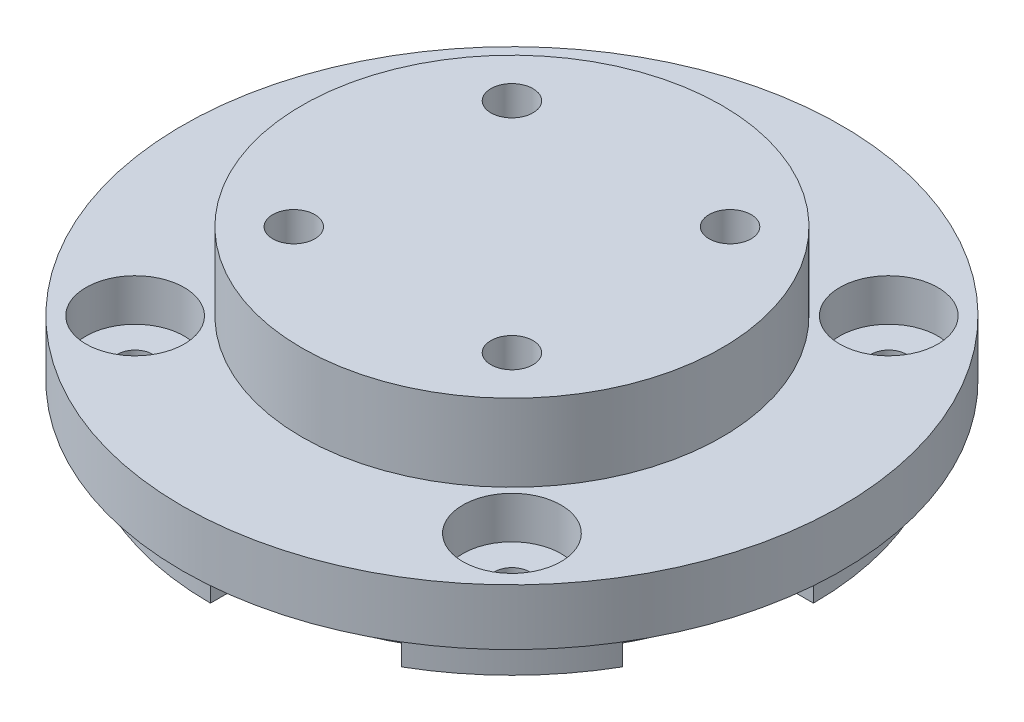
SolidWorks part; units mm, degrees
material "ABS"
ref_plane "前视基准面" through (0, 0, 0) normal (0, 0, 1) x (1, 0, 0)
ref_plane "上视基准面" through (0, 0, 0) normal (0, 1, 0) x (1, 0, 0)
ref_plane "右视基准面" through (0, 0, 0) normal (1, 0, 0) x (0, 0, -1)
other "Configuration Table"
sketch "草图2" plane through (0, 0, 0) normal (0, 1, 0) x (1, 0, 0)
  circle A0 centre (0, 0) radius 21.5
  dimension "D1" = 43
extrude "凸台-拉伸1" add sketch "草图2" along normal blind 7
sketch "草图3" plane through (0, 7, 0) normal (0, 1, 0) x (1, 0, 0)
  circle A0 centre (0, 0) radius 23.5
  circle A1 centre (0, 0) radius 21.5 construction
  dimension "D1" = 2
extrude "凸台-拉伸2" add sketch "草图3" against normal blind 4
sketch "草图6" plane through (0, 7, 0) normal (0, 1, 0) x (1, 0, 0)
  circle A0 centre (0, 0) radius 19 construction
  circle A1 centre (13.435, 13.435) radius 1.25
  circle A2 centre (13.435, -13.435) radius 1.25
  circle A3 centre (-13.435, -13.435) radius 1.25
  circle A4 centre (-13.435, 13.435) radius 1.25
  circle A5 centre (0, 0) radius 8
  dimension "D1" = 38
  dimension "D2" = 2.5
  dimension "D4" = 16
  dimension "D3" = 4
extrude "切除-拉伸1" cut sketch "草图6" against normal blind 15
sketch "草图7" plane through (0, 7, 0) normal (0, 1, 0) x (1, 0, 0)
  circle A0 centre (-13.435, 13.435) radius 3.5
  circle A1 centre (13.435, 13.435) radius 3.5
  circle A2 centre (13.435, -13.435) radius 3.5
  circle A3 centre (-13.435, -13.435) radius 3.5
  point P12 (0, 0)
  dimension "D1" = 7
  dimension "D2" = 4
sketch "草图9" plane through (0, 7, 0) normal (0, 1, 0) x (1, 0, 0)
  circle A0 centre (0, 0) radius 14.02
  circle A1 centre (0, 0) radius 14.98
  dimension "D1" = 28.04
  dimension "D2" = 29.96
extrude "凸台-拉伸3" add sketch "草图9" along normal blind 5.5
extrude "切除-拉伸3" cut sketch "草图7" against normal blind 3
sketch "草图10" plane through (0, 7, 0) normal (0, 1, 0) x (1, 0, 0)
  circle A0 centre (0, 0) radius 11 construction
  circle A3 centre (7.7782, 7.7782) radius 1.25
  circle A4 centre (7.7782, -7.7782) radius 1.25
  circle A5 centre (-7.7782, -7.7782) radius 1.25
  circle A6 centre (-7.7782, 7.7782) radius 1.25
  dimension "D1" = 22
  dimension "D2" = 2.5
  dimension "D3" = 4
extrude "切除-拉伸4" cut sketch "草图10" against normal blind 22
cosmetic thread "装饰螺纹线1" parameters "D2"=3
cosmetic thread "装饰螺纹线2" parameters "D2"=3
cosmetic thread "装饰螺纹线3" parameters "D2"=3
cosmetic thread "装饰螺纹线4" parameters "D2"=3
sketch "草图11" plane through (0, 0, 0) normal (0, -1, 0) x (1, 0, 0)
  line L0 (0, 0) -> (18.6195, 10.75)
  line L1 (0, 0) -> (21.5, 0)
  line L2 (0, 0) -> (0, 21.5)
  line L3 (10.75, 18.6195) -> (0, 0)
  circle A0 centre (0, 0) radius 19.5
  circle A1 centre (0, 0) radius 21.5 construction
  circle A2 centre (0, 0) radius 21.5
  circle M14 centre (0, 0) radius 21.5
  dimension "D1" = 39
  dimension "D2" = 30
  dimension "D3" = 30
extrude "切除-拉伸5" cut sketch "草图11" against normal up to surface (3 mm away) contours A0 L1 L0 M14 | A0 L3 L2 M14 up to face at (0, 3, 21.5)
sketch "草图12" plane through (0, 7, 0) normal (0, 1, 0) x (1, 0, 0)
  circle A0 centre (7.7782, 7.7782) radius 1.5
  circle A1 centre (7.7782, -7.7782) radius 1.5
  circle A2 centre (-7.7782, -7.7782) radius 1.5
  circle A3 centre (-7.7782, 7.7782) radius 1.5
  circle A4 centre (0, 0) radius 14.02
  dimension "D1" = 3
extrude "凸台-拉伸4" add sketch "草图12" along normal blind 5.5
sketch "草图13" plane through (0, 12.5, 0) normal (0, 1, 0) x (1, 0, 0)
  circle A0 centre (0, 0) radius 14.48
  dimension "D5" = 28.96
extrude "切除-拉伸10" cut sketch "草图13" against normal through all from offset 3
